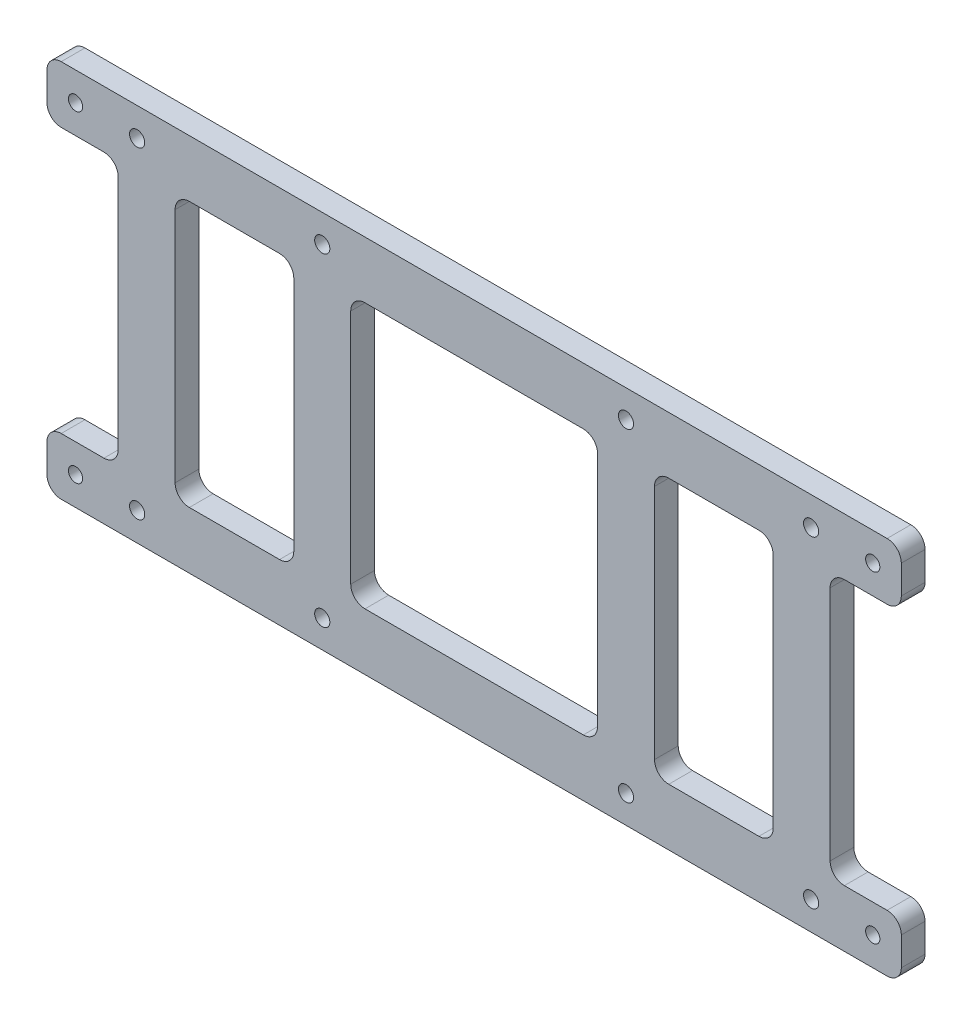
SolidWorks part; units mm, degrees
ref_plane "前视基准面" through (0, 0, 0) normal (0, 0, 1) x (1, 0, 0)
ref_plane "上视基准面" through (0, 0, 0) normal (0, 1, 0) x (1, 0, 0)
ref_plane "右视基准面" through (0, 0, 0) normal (1, 0, 0) x (0, 0, -1)
sketch "草图1" plane through (0, 0, 0) normal (0, 0, 1) x (1, 0, 0)
  line L0 (-8, 27.8432) -> (-8, -28)
  line L2 (-8, 40) -> (-8, 39.8432)
  line L4 (142, 40) -> (142, 39.8432)
  line L5 (-20, 39.8432) -> (154, 39.8432)
  line L6 (-23, 36.8432) -> (-23, 30.8432)
  line L7 (-20, 27.8432) -> (-8, 27.8432)
  line L8 (157, 36.8432) -> (157, 30.8432)
  line L9 (-20, -40) -> (154, -40)
  line L10 (-23, -37) -> (-23, -31)
  line L11 (-20, -28) -> (-8, -28)
  line L12 (157, -37) -> (157, -31)
  line L13 (142, 27.8432) -> (154, 27.8432)
  line L14 (142, -28) -> (154, -28)
  line L15 (142, 27.8432) -> (142, -28)
  line L17 (7, 27.8432) -> (127, 27.8432)
  line L18 (4, 24.8432) -> (4, -25)
  line L19 (7, -28) -> (127, -28)
  line L20 (130, 24.8432) -> (130, -25)
  arc A0 (154, -40) -> (157, -37) centre (154, -37) ccw
  arc A1 (154, -28) -> (157, -31) centre (154, -31) cw
  arc A2 (154, 27.8432) -> (157, 30.8432) centre (154, 30.8432) ccw
  arc A3 (154, 39.8432) -> (157, 36.8432) centre (154, 36.8432) cw
  arc A4 (-20, -40) -> (-23, -37) centre (-20, -37) cw
  arc A5 (-23, -31) -> (-20, -28) centre (-20, -31) cw
  arc A6 (-23, 30.8432) -> (-20, 27.8432) centre (-20, 30.8432) ccw
  arc A7 (-20, 39.8432) -> (-23, 36.8432) centre (-20, 36.8432) ccw
  arc A8 (127, -28) -> (130, -25) centre (127, -25) ccw
  arc A9 (127, 27.8432) -> (130, 24.8432) centre (127, 24.8432) cw
  arc A10 (4, -25) -> (7, -28) centre (7, -25) ccw
  arc A11 (7, 27.8432) -> (4, 24.8432) centre (7, 24.8432) ccw
  point P20 (157, -40)
  point P23 (157, -28)
  point P26 (157, 27.8432)
  point P29 (157, 39.8432)
  dimension "D7" = 3
  dimension "D10" = 3
  dimension "D1" = 15
  dimension "D2" = 15
  dimension "D3" = 15
  dimension "D4" = 15
  dimension "D5" = 12
  dimension "D6" = 12
  dimension "D8" = 12
  dimension "D9" = 12
  dimension "D11" = 150
extrude "凸台-拉伸1" add sketch "草图1" along normal blind 5 contours L5 A7 L6 A6 L7 L0 L11 A5 L10 A4 L9 A0 L12 A1 L14 L15 L13 A2 L8 A3 A11 L17 A9 L20 A8 L19 A10 L18
fillet "圆角1" radius 3 4 edges at (-8, -28, 2.5) (-8, 27.8432, 2.5) (142, -28, 2.5) (142, 27.8432, 2.5)
sketch "草图2" plane through (0, 0, 5) normal (0, 0, 1) x (1, 0, 0)
  line L0 (67, 39.8432) -> (67, -40) construction
  line L1 (-20, 39.8432) -> (154, 39.8432) construction
  line L2 (-20, -40) -> (154, -40) construction
  line L3 (-8, -0.0784) -> (142, -0.0784) construction
  line L4 (-8, 24.8432) -> (-8, -25) construction
  line L5 (142, 24.8432) -> (142, -25) construction
  line L6 (31.0016, 40) -> (39.0016, 40) construction
  line L7 (31.0016, -40) -> (31.0016, 40) construction
  circle A0 centre (-16.978, 33.8432) radius 1.5
  circle A1 centre (-4, 33.8432) radius 1.6
  circle A2 centre (35.0016, 34) radius 1.6
  circle A3 centre (98.9984, 34) radius 1.6
  circle A4 centre (138, 33.8432) radius 1.6
  circle A5 centre (150.978, 33.8432) radius 1.5
  circle A6 centre (150.978, -34) radius 1.5
  circle A7 centre (138, -34) radius 1.6
  circle A8 centre (98.9984, -34.1568) radius 1.6
  circle A9 centre (35.0016, -34.1568) radius 1.6
  circle A10 centre (-4, -34) radius 1.6
  circle A11 centre (-16.978, -34) radius 1.5
  dimension "D1" = 3
  dimension "D2" = 3.2
  dimension "D3" = 3.2
  dimension "D4" = 6
  dimension "D5" = 6
  dimension "D6" = 6
  dimension "D7" = 4
  dimension "D8" = 4
extrude "切除-拉伸1" cut sketch "草图2" against normal blind 7
sketch "草图3" plane through (0, 0, 0) normal (0, 0, -1) x (-1, 0, 0)
  line L0 (-7, 27.8432) -> (-127, 27.8432) construction
  line L1 (-104.9984, 27.8432) -> (-92.9984, 27.8432)
  line L2 (-104.9984, 27.8432) -> (-104.9984, -28)
  line L3 (-104.9984, -28) -> (-92.9984, -28)
  line L4 (-92.9984, 27.8432) -> (-92.9984, -28)
  line L5 (-7, -28) -> (-127, -28) construction
  line L6 (-39.0016, 40) -> (-39.0016, -40) construction
  line L7 (-41.0016, 27.8432) -> (-29.0016, 27.8432)
  line L8 (-41.0016, 27.8432) -> (-41.0016, -28)
  line L9 (-41.0016, -28) -> (-29.0016, -28)
  line L10 (-29.0016, 27.8432) -> (-29.0016, -28)
  line L11 (-102.9984, -40) -> (-102.9984, 40) construction
  dimension "D1" = 12
  dimension "D2" = 12
  dimension "D3" = 2
  dimension "D4" = 2
extrude "凸台-拉伸2" add sketch "草图3" against normal blind 5
fillet "圆角2" radius 3 8 edges at (41.0016, 27.8432, 2.5) (41.0016, -28, 2.5) (92.9984, -28, 2.5) (29.0016, -28, 2.5) (29.0016, 27.8432, 2.5) (92.9984, 27.8432, 2.5) (104.9984, -28, 2.5) (104.9984, 27.8432, 2.5)
